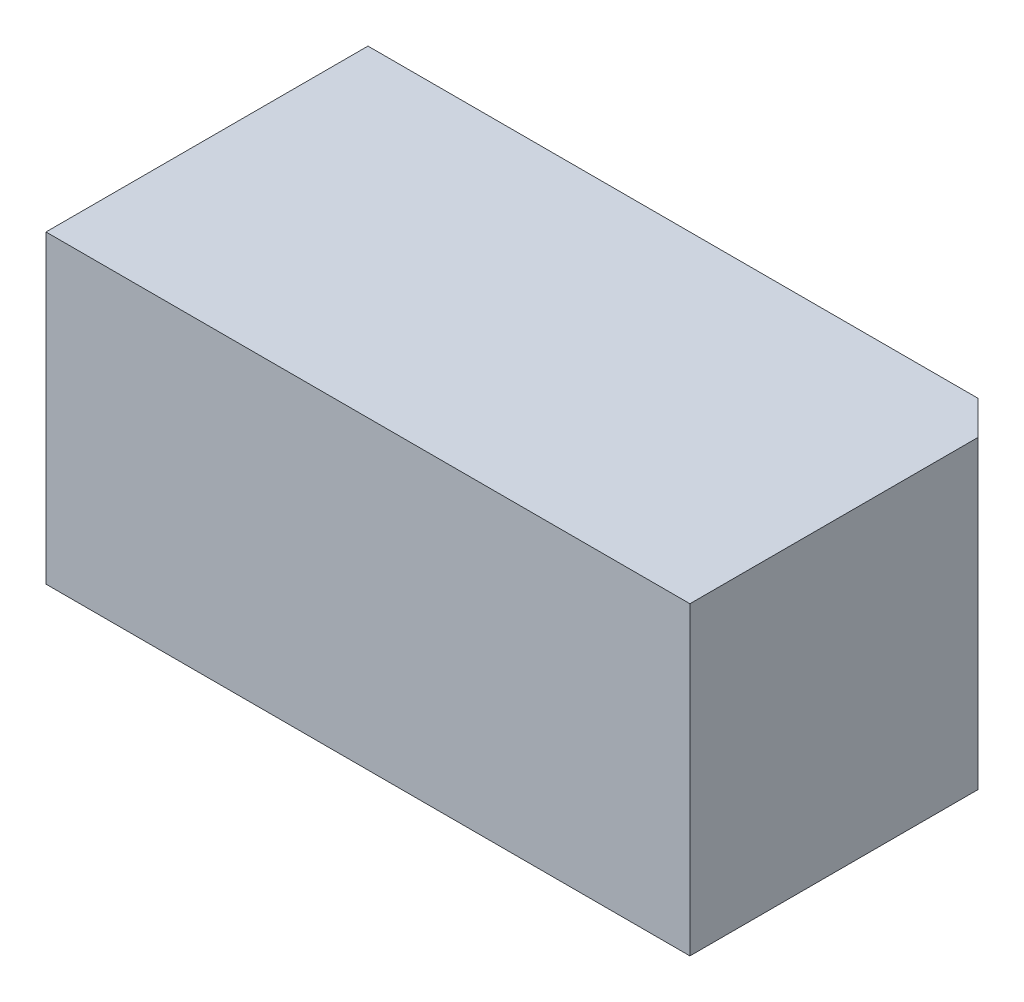
SolidWorks part; units mm, degrees
ref_plane "Спереди" through (0, 0, 0) normal (0, 0, 1) x (1, 0, 0)
ref_plane "Сверху" through (0, 0, 0) normal (0, 1, 0) x (1, 0, 0)
ref_plane "Справа" through (0, 0, 0) normal (1, 0, 0) x (0, 0, -1)
sketch "Эскиз1" plane through (0, 0, 0) normal (0, 1, 0) x (1, 0, 0)
  line L0 (19, -9.5) -> (19, 7.5)
  line L1 (-19, -9.5) -> (19, -9.5)
  line L2 (-19, -9.5) -> (-19, 9.5)
  line L3 (-19, 9.5) -> (19, 9.5) construction
  line L4 (19, -9.5) -> (19, 9.5) construction
  line L5 (-19, -9.5) -> (19, 9.5) construction
  line L6 (-19, 9.5) -> (19, -9.5) construction
  line L7 (-19, 9.5) -> (17, 9.5)
  line L8 (17, 9.5) -> (19, 7.5)
  point P0 (0, 0)
  dimension "D1" = 19
  dimension "D2" = 2
  dimension "D3" = 38
  dimension "D4" = 2
extrude "Бобышка-Вытянуть1" add sketch "Эскиз1" along normal blind 18
sketch "Эскиз2" plane through (0, 0, 0) normal (0, -1, 0) x (1, 0, 0)
  line L0 (-16.1695, 0) -> (23.9474, 0) construction
  line L1 (0, 11.9043) -> (0, -16.3368) construction
  line L2 (-15.75, 12.5369) -> (-15.75, -12.7709) construction
  line L3 (15.75, 11.991) -> (15.75, -15.1885) construction
  circle A0 centre (-15.75, 5.35) radius 0.4
  circle A1 centre (-15.75, -5.35) radius 0.4
  circle A2 centre (15.75, 4.05) radius 0.4
  circle A3 centre (15.75, -4.05) radius 0.4
  dimension "D7" = 0.8
  dimension "D8" = 0.8
  dimension "D9" = 0.8
  dimension "D10" = 0.8
  dimension "D1" = 10.7
  dimension "D2" = 5.35
  dimension "D3" = 31.5
  dimension "D4" = 15.75
  dimension "D5" = 8.1
  dimension "D6" = 4.05
extrude "Бобышка-Вытянуть2" add sketch "Эскиз2" along normal blind 2
equation "\"D2@Эскиз2\"=\"D1@Эскиз2\"/2"
equation "\"D4@Эскиз2\"=\"D3@Эскиз2\"/2"
equation "\"D6@Эскиз2\"=\"D5@Эскиз2\"/2"
equation "\"D8@Эскиз2\"=\"D7@Эскиз2\""
equation "\"D9@Эскиз2\"=\"D7@Эскиз2\""
equation "\"D10@Эскиз2\"=\"D7@Эскиз2\""
